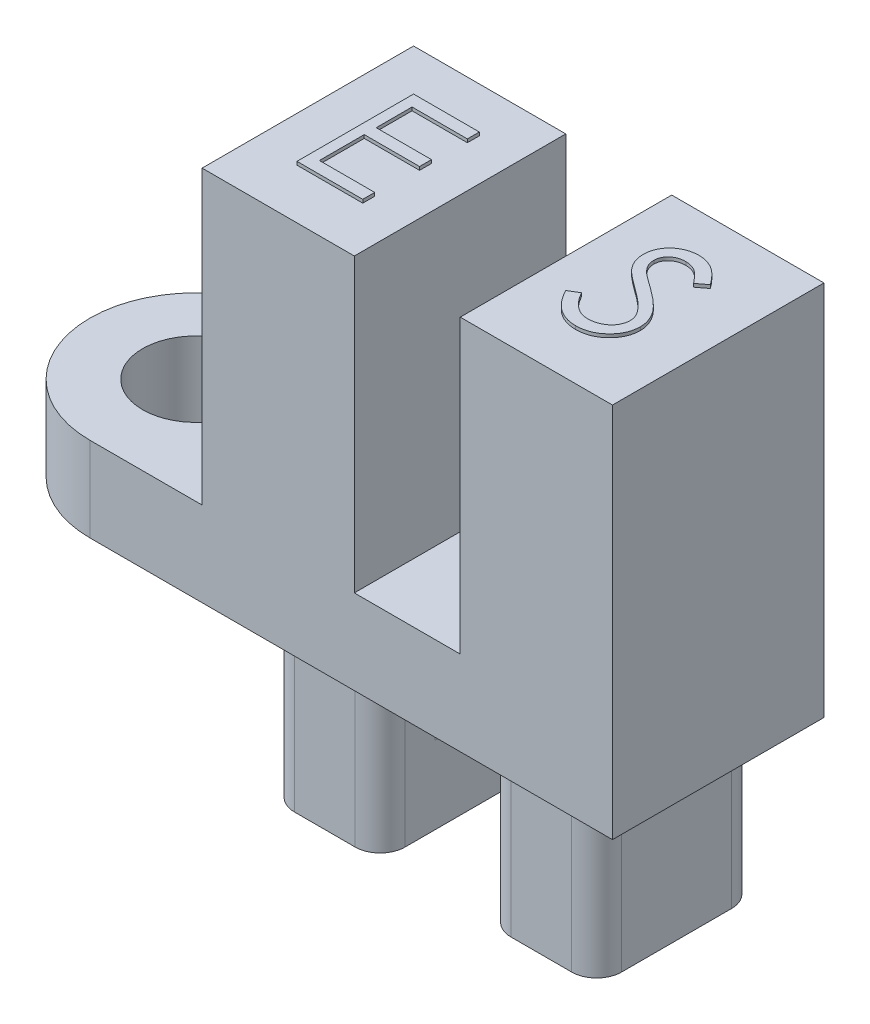
SolidWorks part; units mm, degrees
ref_plane "Front Plane" through (0, 0, 0) normal (0, 0, 1) x (1, 0, 0)
ref_plane "Top Plane" through (0, 0, 0) normal (0, 1, 0) x (1, 0, 0)
ref_plane "Right Plane" through (0, 0, 0) normal (1, 0, 0) x (0, 0, -1)
sketch "Sketch1" plane through (0, 0, 0) normal (0, 1, 0) x (1, 0, 0)
  line L0 (0, 6.2271) -> (0, -7.4076) construction
  line L1 (-9.2668, 0) -> (10.8605, 0) construction
  line L4 (-9.53, 3.1745) -> (0, 3.1745)
  line L5 (-9.53, -3.1745) -> (0, -3.1745)
  line L6 (0, 3.1745) -> (6.16, 3.1745)
  line L7 (6.16, 3.1745) -> (6.16, -3.1745)
  line L8 (6.16, -3.1745) -> (0, -3.1745)
  circle A0 centre (-9.53, 0) radius 1.59
  arc A1 (-9.53, 3.1745) -> (-9.53, -3.1745) centre (-9.53, 0) ccw
  point P8 (0, -3.1745)
  point P16 (0, 3.1745)
  dimension "D1" = 3.18
  dimension "D2" = 9.53
  dimension "D3" = 6.349
  dimension "D4" = 6.16
extrude "Boss-Extrude1" add sketch "Sketch1" along normal blind 2.54
sketch "Sketch2" plane through (0, 2.54, 0) normal (0, 1, 0) x (1, 0, 0)
  line L0 (0, 3.1745) -> (0, -3.1745) construction
  line L1 (6.16, -3.1745) -> (6.16, 3.1745) construction
  line L3 (-1.59, 3.1745) -> (-1.59, -3.1745)
  line L4 (-6.16, 3.1745) -> (-6.16, -3.1745)
  line L5 (-6.16, 3.1745) -> (-1.59, 3.1745)
  line L6 (-6.16, -3.1745) -> (-1.59, -3.1745)
  line L7 (6.16, 3.1745) -> (6.16, -3.1745)
  line L8 (6.16, 3.1745) -> (1.59, 3.1745)
  line L9 (1.59, 3.1745) -> (1.59, -3.1745)
  line L10 (6.16, -3.1745) -> (1.59, -3.1745)
  line L12 (6.16, 3.1745) -> (-9.53, 3.1745) construction
  line L13 (-9.53, -3.1745) -> (6.16, -3.1745) construction
  point P2 (0, 0)
  point P3 (0, 0)
  point P4 (0, 0)
  point P5 (0, 0)
  point P14 (-1.59, 3.1745)
  point P15 (-1.59, 3.1745)
  point P16 (0, 3.1745)
  point P17 (0, 0)
  point P18 (0, 2.1656)
  point P21 (0, 0)
  point P22 (0, 0)
  point P23 (0, 0)
  point P26 (0, 0)
  point P27 (0, 0)
  point P28 (0, 0)
  dimension "D1" = 3.18
  dimension "D2" = 6.16
extrude "Boss-Extrude2" add sketch "Sketch2" along normal blind 8.76
sketch "Sketch3" plane through (0, 0, 0) normal (0, -1, 0) x (1, 0, 0)
  line L0 (0, 3.1745) -> (0, -3.1745) construction
  line L3 (-5.2064, 0) -> (6.1252, 0) construction
  line L4 (4.91, 2.4) -> (1.59, 2.4)
  line L5 (-4.91, -2.4) -> (-1.59, -2.4)
  line L6 (-4.91, -2.4) -> (-4.91, 2.4)
  line L7 (-4.91, 2.4) -> (-1.59, 2.4)
  line L8 (-1.59, -2.4) -> (-1.59, 2.4)
  line L9 (-4.91, -2.4) -> (-1.59, 2.4) construction
  line L10 (-4.91, 2.4) -> (-1.59, -2.4) construction
  line L11 (1.59, -2.4) -> (1.59, 2.4)
  line L12 (4.91, -2.4) -> (1.59, -2.4)
  line L13 (4.91, -2.4) -> (4.91, 2.4)
  line L14 (6.16, 3.1745) -> (6.16, -3.1745) construction
  line L15 (6.16, -3.1745) -> (-9.53, -3.1745) construction
  line L16 (-9.53, 3.1745) -> (6.16, 3.1745) construction
  point P4 (0, 0)
  point P7 (-3.25, 0)
  point P18 (0, 0)
  point P20 (0, 0)
  dimension "D1" = 3.18
  dimension "D2" = 4.8
  dimension "D3" = 3.32
  dimension "D4" = 6.16
extrude "Boss-Extrude3" add sketch "Sketch3" along normal blind 4.83
sketch "Sketch6" plane through (0, 0, 0) normal (0, 0, 1) x (1, 0, 0)
  line L0 (1.59, -4.83) -> (1.59, 0) construction
  line L1 (-1.59, -4.83) -> (-1.59, 0) construction
  line L3 (-1.59, -2.5) -> (-1.59, 0)
  line L4 (-1.59, 0) -> (1.59, 0)
  line L5 (1.59, 0) -> (1.59, -2.5)
  arc A0 (1.59, -2.5) -> (-1.59, -2.5) centre (0, -2.5) ccw
  point P7 (0, 0)
  dimension "D1" = 2.5
extrude "Boss-Extrude5" add sketch "Sketch6" along normal blind 0.75 and the other way blind 0.75
sketch "Sketch7" plane through (0, 0, 0) normal (0, -1, 0) x (1, 0, 0)
  line L0 (4.91, 2.4) -> (1.59, 2.4) construction
  line L1 (5.41, -2.9) -> (-5.41, -2.9)
  line L2 (5.41, -2.9) -> (5.41, 2.9)
  line L3 (5.41, 2.9) -> (-5.41, 2.9)
  line L4 (-5.41, -2.9) -> (-5.41, 2.9)
  line L5 (5.41, -2.9) -> (-5.41, 2.9) construction
  line L6 (5.41, 2.9) -> (-5.41, -2.9) construction
  line L7 (4.91, -2.4) -> (4.91, 2.4) construction
  line L9 (-5.31, -2.8) -> (5.31, -2.8)
  line L10 (-5.31, -2.8) -> (-5.31, 2.8)
  line L11 (-5.31, 2.8) -> (5.31, 2.8)
  line L12 (5.31, -2.8) -> (5.31, 2.8)
  line L13 (-5.31, -2.8) -> (5.31, 2.8) construction
  line L14 (-5.31, 2.8) -> (5.31, -2.8) construction
  point P0 (0, 0)
  point P10 (0, 0)
  dimension "D1" = 0.5
  dimension "D2" = 0.5
  dimension "D3" = 0.1
  dimension "D4" = 0.1
extrude "Cut-Extrude1" cut sketch "Sketch7" against normal blind 0.2
fillet "Fillet1" radius 0.75 8 edges at (4.91, -2.415, -2.4) (1.59, -2.415, 2.4) (1.59, -2.415, -2.4) (4.91, -2.415, 2.4) (-1.59, -2.415, 2.4) (-1.59, -2.415, -2.4) (-4.91, -2.415, -2.4) (-4.91, -2.415, 2.4)
sketch "Sketch8" plane through (0, 11.3, 0) normal (0, 1, 0) x (1, 0, 0)
  line L0 (-6.16, -3.1745) -> (-1.59, -3.1745) construction
  line L1 (-6.16, 3.1745) -> (-6.16, -3.1745) construction
  line L2 (1.59, 3.1745) -> (1.59, -3.1745) construction
  text T0 "E" font "Century Gothic" height 3.5
  text T1 "S"
  dimension "D1" = 1.5
  dimension "D2" = 0.9
  dimension "D3" = 0.9
extrude "Boss-Extrude6" add sketch "Sketch8" along normal blind 0.1
